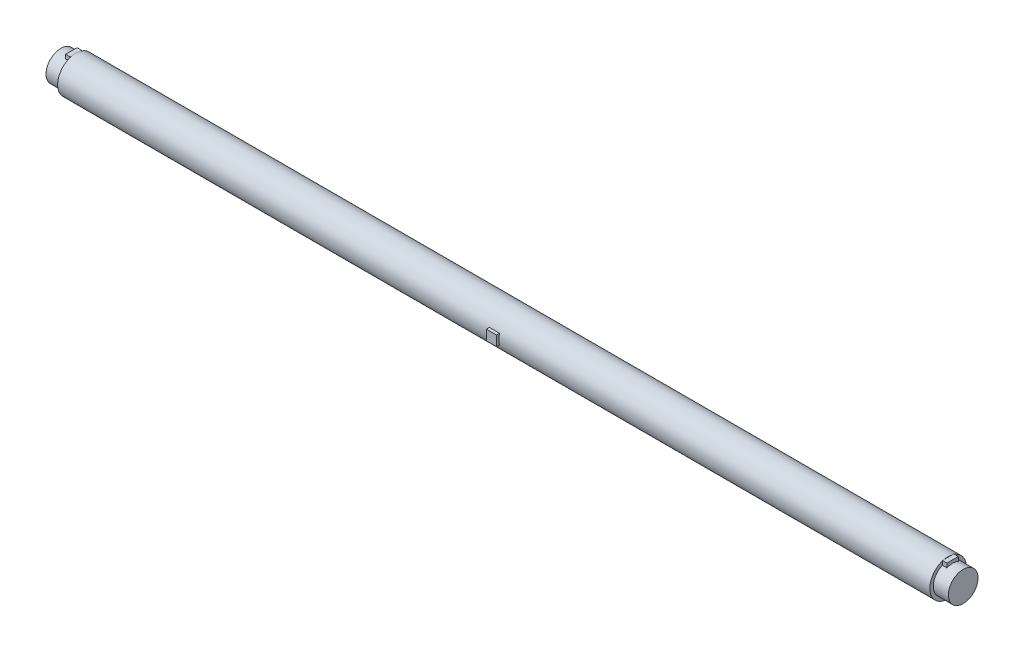
SolidWorks part; units mm, degrees
ref_plane "Front Plane" through (0, 0, 0) normal (0, 0, 1) x (1, 0, 0)
ref_plane "Top Plane" through (0, 0, 0) normal (0, 1, 0) x (1, 0, 0)
ref_plane "Right Plane" through (0, 0, 0) normal (1, 0, 0) x (0, 0, -1)
sketch "Sketch1" plane through (0, 0, 0) normal (0, 0, 1) x (1, 0, 0)
  line L0 (-988, 0) -> (-988, 32.5)
  line L1 (-988, 32.5) -> (-955, 32.5)
  line L2 (-955, 32.5) -> (-955, 40)
  line L3 (-955, 40) -> (955, 40)
  line L4 (955, 40) -> (955, 32.5)
  line L5 (955, 32.5) -> (988, 32.5)
  line L6 (988, 32.5) -> (988, 0)
  line L7 (988, 0) -> (-988, 0)
  dimension "D1" = 1976
  dimension "D2" = 33
  dimension "D3" = 33
  dimension "D4" = 32.5
  dimension "D5" = 40
  dimension "D6" = 32.5
  dimension "D7" = 988
revolve "Revolve1" add sketch "Sketch1" angle 360 about L7
ref_plane "Plane1" through (0, 0, 45.1) normal (0, 0, 1) x (1, 0, 0)
sketch "Sketch4" plane through (0, 0, 45.1) normal (0, 0, 1) x (1, 0, 0)
  line L1 (-11.18, 11) -> (11.18, 11)
  line L2 (-11.18, 11) -> (-11.18, -11)
  line L3 (-11.18, -11) -> (11.18, -11)
  line L4 (11.18, 11) -> (11.18, -11)
  dimension "D1" = 22.36
  dimension "D2" = 11
  dimension "D3" = 22
  dimension "D4" = 11.18
extrude "Boss-Extrude1" add sketch "Sketch4" against normal up to surface (6.6422 mm away)
sketch "Sketch5" plane through (-955, 0, 0) normal (-1, 0, 0) x (0, 0, 1)
  line L2 (-12.5, 30) -> (-12.5, 39.13)
  line L3 (-12.5, 39.13) -> (12.5, 39.13)
  line L4 (12.5, 30) -> (12.5, 39.13)
  line L5 (0, 32.5) -> (12.5, 39.13) construction
  line L6 (-12.5, 39.13) -> (0, 32.5) construction
  circle A0 centre (0, 0) radius 32.5 construction
  circle A1 centre (0, 0) radius 32.5 construction
  arc A2 (12.5, 30) -> (-12.5, 30) centre (0, 0) ccw
  point P0 (0, 32.5)
  dimension "D1" = 25
  dimension "D3" = 9.13
  dimension "D4" = 9.13
extrude "Boss-Extrude2" add sketch "Sketch5" along normal blind 10
ref_plane "Plane2" through (0, 0, 0) normal (-1, 0, 0) x (0, 0, 1)
mirror "Mirror1" about plane through (0, 0, 0) normal (-1, 0, 0) of "Boss-Extrude2"
